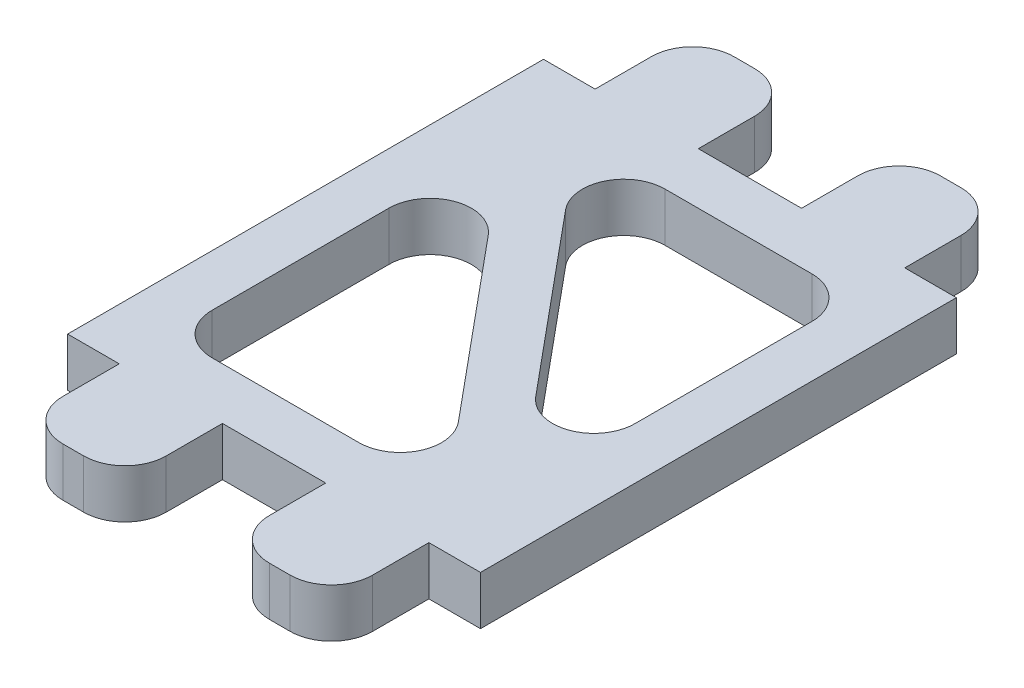
SolidWorks part; units mm, degrees
ref_plane "Front Plane" through (0, 0, 0) normal (0, 0, 1) x (1, 0, 0)
ref_plane "Top Plane" through (0, 0, 0) normal (0, 1, 0) x (1, 0, 0)
ref_plane "Right Plane" through (0, 0, 0) normal (1, 0, 0) x (0, 0, -1)
sketch "Sketch1" plane through (0, 0, 0) normal (0, 1, 0) x (1, 0, 0)
  line L1 (12.7, -14.6375) -> (-12.7, -14.6375)
  line L2 (12.7, -14.6375) -> (12.7, 14.6375)
  line L3 (12.7, 14.6375) -> (-12.7, 14.6375)
  line L4 (-12.7, -14.6375) -> (-12.7, 14.6375)
  line L5 (12.7, -14.6375) -> (-12.7, 14.6375) construction
  line L6 (12.7, 14.6375) -> (-12.7, -14.6375) construction
  point P0 (0, 0)
  dimension "D1" = 25.4
  dimension "D2" = 29.275
extrude "Boss-Extrude1" add sketch "Sketch1" along normal blind 3
sketch "Sketch2" plane through (0, 0, 14.6375) normal (0, 0, 1) x (1, 0, 0)
  line L0 (-12.7, 3) -> (12.7, 3) construction
  line L1 (-9.525, 3) -> (-3.175, 3)
  line L2 (-9.525, 3) -> (-9.525, 0)
  line L3 (-9.525, 0) -> (-3.175, 0)
  line L4 (-3.175, 3) -> (-3.175, 0)
  line L5 (-12.7, 0) -> (12.7, 0) construction
  line L6 (-12.7, 3) -> (-12.7, 0) construction
  dimension "D1" = 6.35
  dimension "D2" = 3.175
extrude "Boss-Extrude2" add sketch "Sketch2" along normal blind 6
pattern_linear "LPattern1" count 2 spacing 12.7 along (1, 0, 0) of "Boss-Extrude2"
mirror "Mirror1" about plane through (0, 0, 0) normal (0, 0, 1) of "LPattern1", "Boss-Extrude2"
sketch "Sketch4" plane through (0, 3, 0) normal (0, 1, 0) x (1, 0, 0)
  line L0 (-9.525, 11.4625) -> (-9.525, -11.4625)
  line L1 (-12.7, 14.6375) -> (12.7, 14.6375) construction
  line L2 (-12.7, 14.6375) -> (-12.7, -14.6375) construction
  line L3 (-12.7, -14.6375) -> (12.7, -14.6375) construction
  line L4 (12.7, 14.6375) -> (12.7, -14.6375) construction
  line L5 (-9.525, -11.4625) -> (9.525, -11.4625)
  line L6 (9.525, 11.4625) -> (9.525, -11.4625)
  line L7 (-9.525, 11.4625) -> (9.525, 11.4625)
  line L8 (-9.525, 11.4625) -> (9.525, -11.4625) construction
  line L9 (-10.746, 10.4479) -> (8.304, -12.4771)
  line L10 (-8.304, 12.4771) -> (10.746, -10.4479)
  dimension "D1" = 3.175
  dimension "D2" = 1.5875
  dimension "D3" = 1.5875
extrude "Cut-Extrude1" cut sketch "Sketch4" against normal through all both and the other way through all contours L9 L0 L5 | L7 L10 L6
fillet "Fillet1" radius 2.54 6 edges at (9.525, 1.5, -11.4625) (9.525, 1.5, 8.9786) (7.4609, 1.5, 11.4625) (-9.525, 1.5, 11.4625) (-9.525, 1.5, -8.9786) (-7.4609, 1.5, -11.4625)
fillet "Fillet2" radius 2.54 8 edges at (-9.525, 1.5, 20.6375) (-3.175, 1.5, 20.6375) (3.175, 1.5, 20.6375) (9.525, 1.5, 20.6375) (-9.525, 1.5, -20.6375) (-3.175, 1.5, -20.6375) (3.175, 1.5, -20.6375) (9.525, 1.5, -20.6375)
